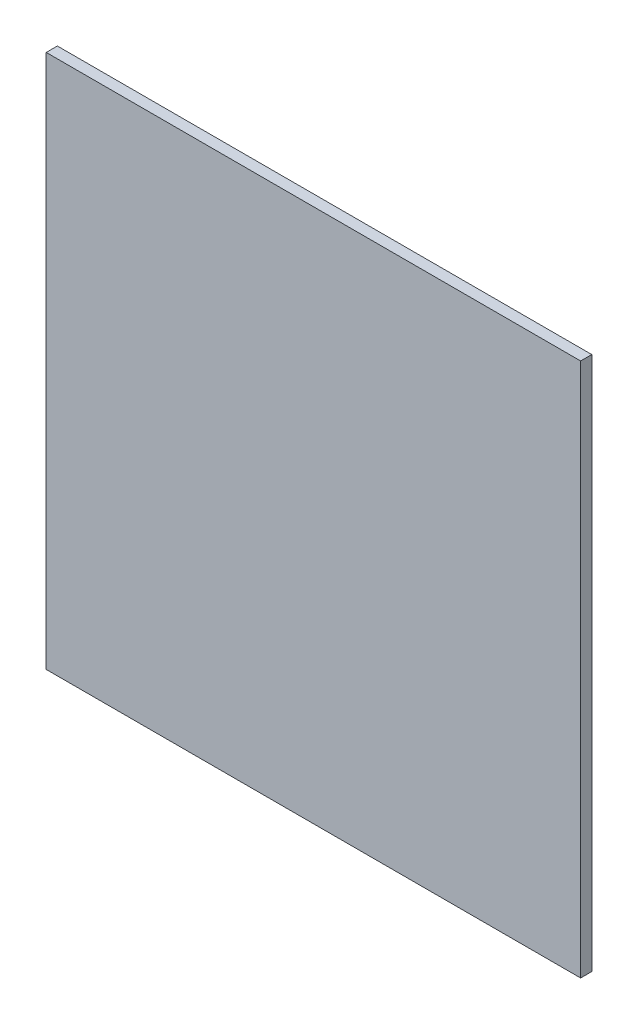
SolidWorks part; units mm, degrees
ref_plane "Front Plane" through (0, 0, 0) normal (0, 0, 1) x (1, 0, 0)
ref_plane "Top Plane" through (0, 0, 0) normal (0, 1, 0) x (1, 0, 0)
ref_plane "Right Plane" through (0, 0, 0) normal (1, 0, 0) x (0, 0, -1)
sketch "Sketch1" plane through (0, 0, 0) normal (0, 0, 1) x (1, 0, 0)
  line L1 (0, 0) -> (96, 0)
  line L2 (0, 0) -> (0, 96)
  line L3 (0, 96) -> (96, 96)
  line L4 (96, 0) -> (96, 96)
  dimension "D1" = 96
  dimension "D2" = 96
extrude "Boss-Extrude2" add sketch "Sketch1" along normal blind 2 contours L2 L1 L4 L3
sketch "Finger Opening Hole" plane through (0, 0, 2) normal (0, 0, 1) x (1, 0, 0)
  line L0 (48, 96) -> (48, 88) construction
  line L1 (0, 96) -> (96, 96) construction
  line L2 (48, 88) -> (55.5, 88) construction
  line L3 (48, 88) -> (40.5, 88) construction
  line L5 (40.5, 88) -> (55.5, 88)
  line L6 (40.5, 88) -> (40.5, 96)
  line L7 (40.5, 96) -> (55.5, 96)
  line L8 (55.5, 88) -> (55.5, 96)
  dimension "D1" = 8
  dimension "D2" = 7.5
  dimension "D3" = 7.5
sketch "Airflow" plane through (0, 0, 2) normal (0, 0, 1) x (1, 0, 0)
  line L0 (0, 48) -> (96, 48) construction
  line L1 (0, 0) -> (0, 96) construction
  line L2 (96, 0) -> (96, 96) construction
  line L3 (48, 0) -> (48, 96) construction
  line L4 (0, 0) -> (96, 0) construction
  line L5 (0, 0) -> (4, 0) construction
  line L6 (0, 0) -> (0, 4) construction
  line L7 (0, 4) -> (4, 4) construction
  line L8 (4, 4) -> (4, 0) construction
  line L9 (96, 0) -> (92, 0) construction
  line L10 (96, 0) -> (96, 4) construction
  line L11 (92, 0) -> (92, 4) construction
  line L12 (92, 4) -> (96, 4) construction
  line L13 (4, 4) -> (92, 4) construction
  line L14 (4, 4) -> (4, 96) construction
  line L15 (0, 96) -> (96, 96) construction
  line L16 (0, 96) -> (0, 84) construction
  line L17 (0, 84) -> (96, 84) construction
  line L18 (92, 4) -> (92, 96) construction
  line L19 (10, 4) -> (10, 84)
  line L20 (4, 4) -> (8, 4)
  line L21 (4, 4) -> (4, 84)
  line L22 (4, 84) -> (8, 84)
  line L23 (8, 4) -> (8, 84)
  line L24 (10, 4) -> (14, 4)
  line L25 (14, 4) -> (14, 84)
  line L26 (10, 84) -> (14, 84)
  line L27 (16, 4) -> (16, 84)
  line L28 (16, 4) -> (20, 4)
  line L29 (20, 4) -> (20, 84)
  line L30 (16, 84) -> (20, 84)
  line L31 (22, 4) -> (22, 84)
  line L32 (22, 4) -> (26, 4)
  line L33 (26, 4) -> (26, 84)
  line L34 (22, 84) -> (26, 84)
  line L35 (28, 4) -> (28, 84)
  line L36 (28, 4) -> (32, 4)
  line L37 (32, 4) -> (32, 84)
  line L38 (28, 84) -> (32, 84)
  line L39 (34, 4) -> (34, 84)
  line L40 (34, 4) -> (38, 4)
  line L41 (38, 4) -> (38, 84)
  line L42 (34, 84) -> (38, 84)
  line L43 (40, 4) -> (40, 84)
  line L44 (40, 4) -> (44, 4)
  line L45 (44, 4) -> (44, 84)
  line L46 (40, 84) -> (44, 84)
  line L47 (46, 4) -> (46, 84)
  line L48 (46, 4) -> (50, 4)
  line L49 (50, 4) -> (50, 84)
  line L50 (46, 84) -> (50, 84)
  line L51 (52, 4) -> (52, 84)
  line L52 (52, 4) -> (56, 4)
  line L53 (56, 4) -> (56, 84)
  line L54 (52, 84) -> (56, 84)
  line L55 (58, 4) -> (58, 84)
  line L56 (58, 4) -> (62, 4)
  line L57 (62, 4) -> (62, 84)
  line L58 (58, 84) -> (62, 84)
  line L59 (64, 4) -> (64, 84)
  line L60 (64, 4) -> (68, 4)
  line L61 (68, 4) -> (68, 84)
  line L62 (64, 84) -> (68, 84)
  line L63 (70, 4) -> (70, 84)
  line L64 (70, 4) -> (74, 4)
  line L65 (74, 4) -> (74, 84)
  line L66 (70, 84) -> (74, 84)
  line L67 (76, 4) -> (76, 84)
  line L68 (76, 4) -> (80, 4)
  line L69 (80, 4) -> (80, 84)
  line L70 (76, 84) -> (80, 84)
  line L71 (82, 4) -> (82, 84)
  line L72 (82, 4) -> (86, 4)
  line L73 (86, 4) -> (86, 84)
  line L74 (82, 84) -> (86, 84)
  line L75 (88, 4) -> (88, 84)
  line L76 (88, 4) -> (92, 4)
  line L77 (92, 4) -> (92, 84)
  line L78 (88, 84) -> (92, 84)
  dimension "D1" = 4
  dimension "D2" = 4
  dimension "D3" = 4
  dimension "D4" = 12
  dimension "D5" = 4
  dimension "D6" = 15
equation "\"L\"= 100mm"
equation "\"T\"= 1mm"
equation "\"D1@Sketch1\"=(24/25)*\"L\""
equation "\"D2@Sketch1\"=(24/25)*\"L\""
equation "\"D1@Finger Opening Hole\" = 8 * \"T\""
equation "\"D2@Finger Opening Hole\" = 7.5 * \"T\""
equation "\"D3@Finger Opening Hole\" = 7.5 * \"T\""
equation "\"D1@Airflow\"=4*\"T\""
equation "\"D2@Airflow\"=4*\"T\""
equation "\"D3@Airflow\"=4*\"T\""
equation "\"D4@Airflow\"=12*\"T\""
equation "\"D5@Airflow\"=4*\"T\""
